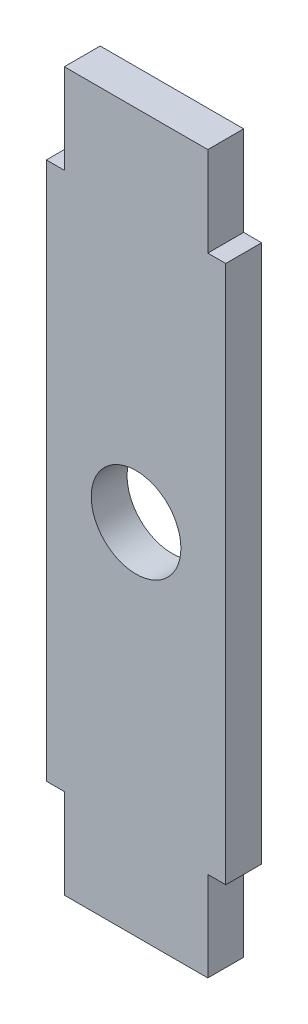
SolidWorks part; units mm, degrees
ref_plane "Front Plane" through (0, 0, 0) normal (0, 0, 1) x (1, 0, 0)
ref_plane "Top Plane" through (0, 0, 0) normal (0, 1, 0) x (1, 0, 0)
ref_plane "Right Plane" through (0, 0, 0) normal (1, 0, 0) x (0, 0, -1)
sketch "Sketch1" plane through (0, 0, 0) normal (0, 0, 1) x (1, 0, 0)
  line L0 (-4, -15) -> (-5, -15)
  line L1 (5, 15) -> (4, 15)
  line L2 (5, 15) -> (5, -15)
  line L3 (5, -15) -> (4, -15)
  line L4 (-5, 15) -> (-5, -15)
  line L5 (5, 15) -> (-5, -15) construction
  line L6 (5, -15) -> (-5, 15) construction
  line L7 (4, -20) -> (-4, -20)
  line L8 (4, -20) -> (4, -15)
  line L9 (4, 20) -> (-4, 20)
  line L10 (-4, -20) -> (-4, -15)
  line L11 (4, -20) -> (-4, 20) construction
  line L12 (4, 20) -> (-4, -20) construction
  line L13 (-4, 15) -> (-4, 20)
  line L14 (4, 15) -> (4, 20)
  line L15 (-4, 15) -> (-5, 15)
  circle A0 centre (0, 0) radius 2.5
  point P0 (0, 0)
  point P6 (0, 0)
  dimension "D1" = 8
  dimension "D2" = 10
  dimension "D3" = 40
  dimension "D4" = 30
extrude "Boss-Extrude1" add sketch "Sketch1" along normal blind 2
